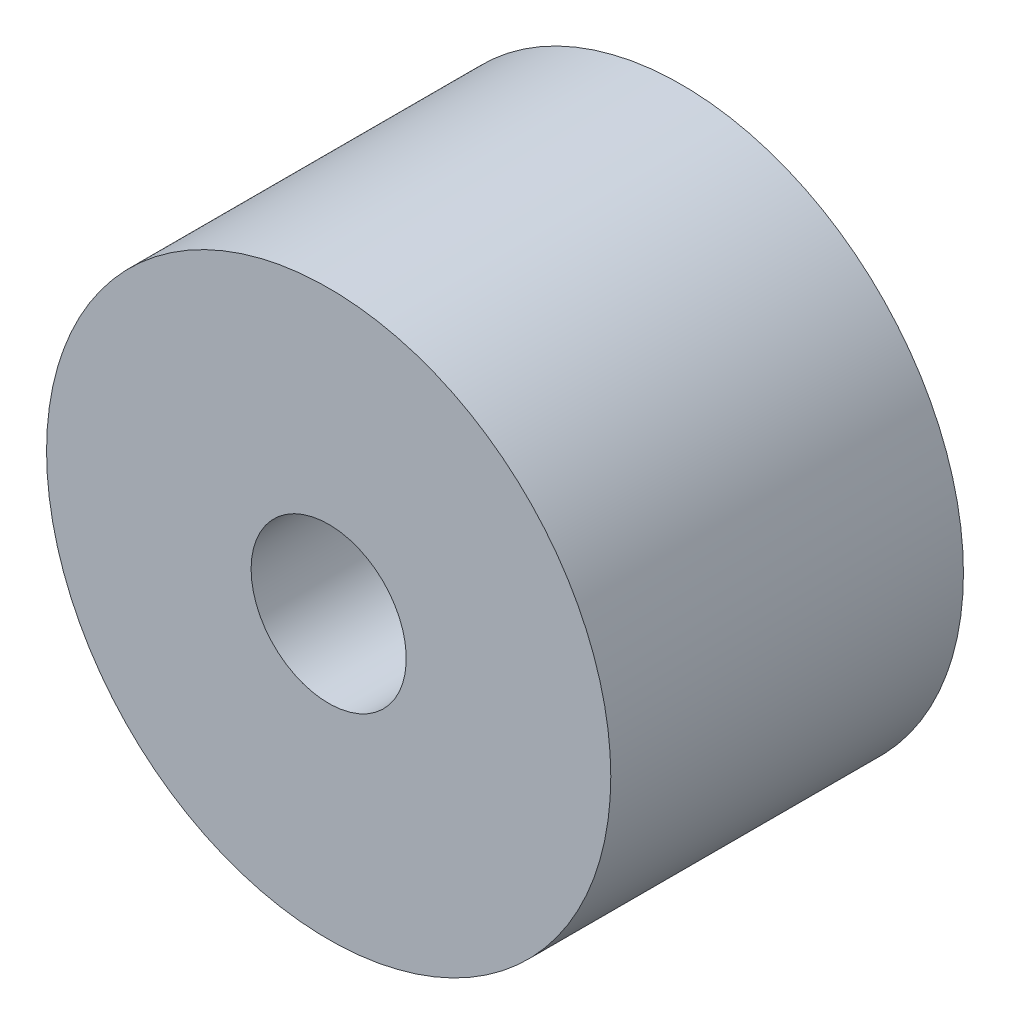
SolidWorks part; units mm, degrees
ref_plane "Front Plane" through (0, 0, 0) normal (0, 0, 1) x (1, 0, 0)
ref_plane "Top Plane" through (0, 0, 0) normal (0, 1, 0) x (1, 0, 0)
ref_plane "Right Plane" through (0, 0, 0) normal (1, 0, 0) x (0, 0, -1)
sketch "Sketch1" plane through (0, 0, 0) normal (0, 0, 1) x (1, 0, 0)
  circle A0 centre (0, 0) radius 2.794
  circle A1 centre (0, 0) radius 10.16
  dimension "D1" = 5.588
  dimension "D2" = 20.32
extrude "Boss-Extrude3" add sketch "Sketch1" along normal blind 12.7
